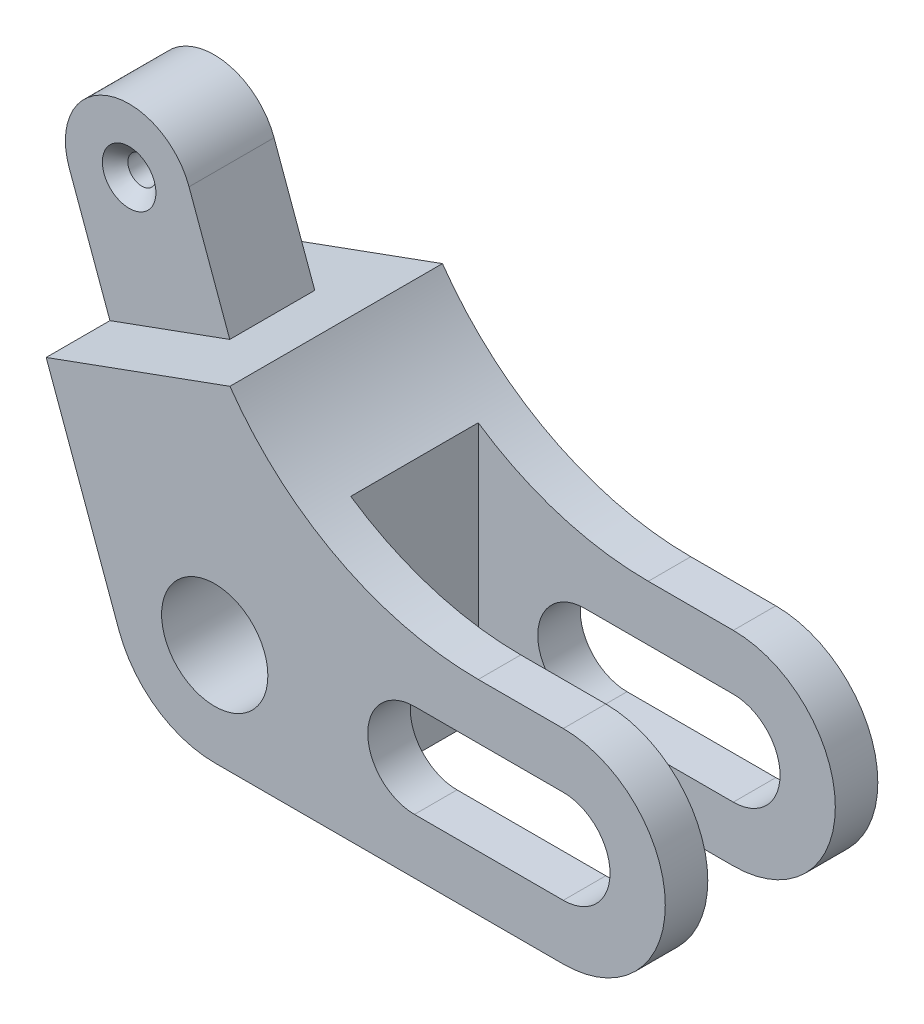
SolidWorks part; units mm, degrees
ref_plane "Front Plane" through (0, 0, 0) normal (0, 0, 1) x (1, 0, 0)
ref_plane "Top Plane" through (0, 0, 0) normal (0, 1, 0) x (1, 0, 0)
ref_plane "Right Plane" through (0, 0, 0) normal (1, 0, 0) x (0, 0, -1)
sketch "Sketch1" plane through (0, 0, 0) normal (0, 0, 1) x (1, 0, 0)
  line L0 (0, -24) -> (82, -24)
  line L1 (82, 24) -> (62, 24)
  line L2 (3.5722, 54.5091) -> (-11.4629, 49.0368)
  line L3 (-39.6536, 38.7761) -> (-22.5526, -8.2085)
  line L4 (-22.5526, -8.2085) -> (-22.5526, 24.6677) construction
  line L5 (47, 11) -> (82, 11)
  line L6 (47, -11) -> (82, -11)
  line L7 (-39.6536, 38.7761) -> (-49.2302, 65.0875)
  line L8 (-21.0394, 75.3481) -> (-11.4629, 49.0368)
  circle A0 centre (0, 0) radius 12.5
  arc A1 (82, -24) -> (82, 24) centre (82, 0) ccw
  arc A2 (62, 24) -> (3.5722, 54.5091) centre (62, 95.2019) cw
  arc A3 (-22.5526, -8.2085) -> (0, -24) centre (0, 0) ccw
  arc A4 (47, 11) -> (47, -11) centre (47, 0) ccw
  arc A5 (82, 11) -> (82, -11) centre (82, 0) cw
  arc A6 (-49.2302, 65.0875) -> (-21.0394, 75.3481) centre (-35.1348, 70.2178) cw
  circle A7 centre (-35.1348, 70.2178) radius 3
  dimension "D1" = 25
  dimension "D3" = 11
  dimension "D4" = 24
  dimension "D11" = 15
  dimension "D12" = 6
  dimension "D2" = 20
  dimension "D5" = 35
  dimension "D6" = 82
  dimension "D7" = 46
  dimension "D8" = 20
  dimension "D9" = 50
  dimension "D10" = 28
  dimension "D13" = 28
extrude "Boss-Extrude1" add sketch "Sketch1" along normal mid plane 50
sketch "Sketch2" plane through (5.6382, 2.0521, 0) normal (0.9397, 0.342, 0) x (0, 0, -1)
  line L0 (25, 93) -> (-25, 93) construction
  line L1 (-25, 50) -> (-10, 50)
  line L2 (-25, 50) -> (-25, 93)
  line L3 (-25, 93) -> (-10, 93)
  line L4 (-10, 50) -> (-10, 93)
  line L6 (25, 50) -> (10, 50)
  line L7 (25, 50) -> (25, 93)
  line L8 (25, 93) -> (10, 93)
  line L9 (10, 50) -> (10, 93)
  dimension "D1" = 20
  dimension "D2" = 10
extrude "Cut-Extrude1" cut sketch "Sketch2" against normal blind 50
sketch "Sketch4" plane through (0, 24, 0) normal (0, 1, 0) x (1, 0, 0)
  line L0 (62, 25) -> (3.5722, 25) construction
  line L1 (22, -15) -> (122, -15)
  line L2 (22, -15) -> (22, 15)
  line L3 (22, 15) -> (122, 15)
  line L4 (122, -15) -> (122, 15)
  line L6 (3.5722, -25) -> (62, -25) construction
  dimension "D1" = 22
  dimension "D2" = 10
  dimension "D3" = 100
  dimension "D4" = 10
extrude "Cut-Extrude2" cut sketch "Sketch4" against normal through all both and the other way through all contours L2 L3 L4 L1
hole_wizard "CSK for M6 Flat Head Machine Screw1" positions "Sketch10" profile "Sketch11" countersink size "M6" standard "ANSI Metric" end condition through all
sketch "Sketch10" plane through (0, 0, 10) normal (0, 0, 1) x (1, 0, 0)
  point P0 (-35.1348, 70.2178)
sketch "Sketch11" plane through (-35.1348, 70.2178, 10) normal (1, 0, 0) x (0, -1, 0)
  line L0 (0, 0) -> (0, 35)
  line L1 (0, 35) -> (3.3, 35)
  line L2 (3.3, 35) -> (3.3, 3)
  line L3 (3.3, 3) -> (6.3, 0)
  line L5 (6.3, 0) -> (0, 0)
  line L6 (-3.3, 3) -> (-6.3, 0) construction
  line L11 (0, -6.35) -> (0, 107.95) construction
  dimension "Thru Hole Dia." = 6.6
  dimension "Thru Hole Depth" = 35
  dimension "Near C'Sink Dia." = 12.6
  dimension "Near C'Sink Angle" = 90
